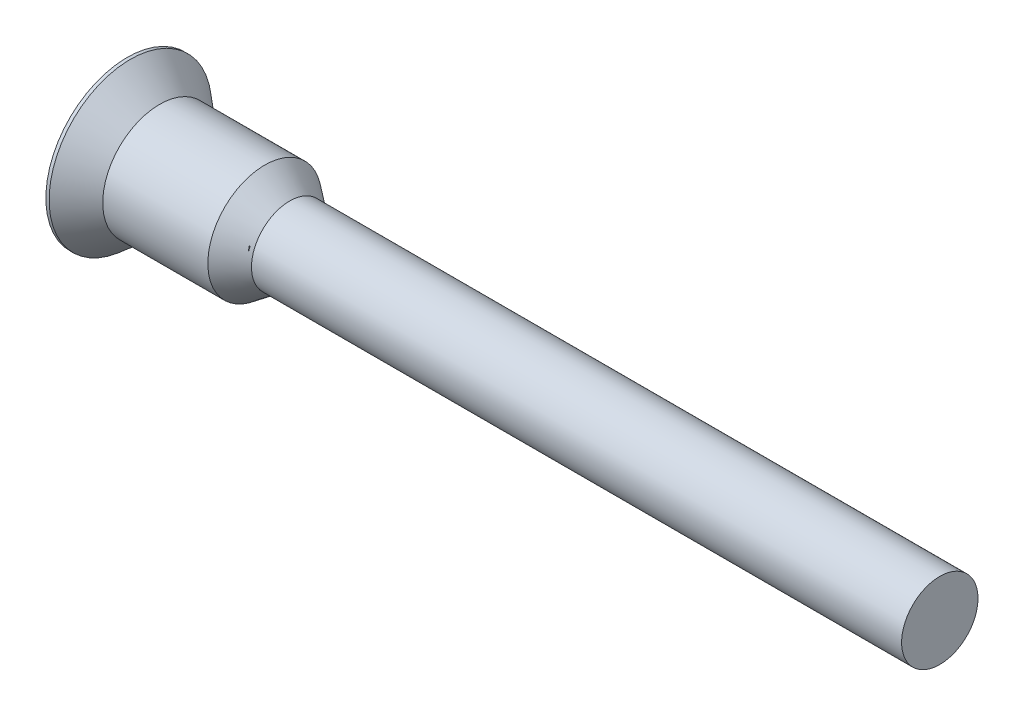
SolidWorks part; units mm, degrees
ref_plane "Front Plane" through (0, 0, 0) normal (0, 0, 1) x (1, 0, 0)
ref_plane "Top Plane" through (0, 0, 0) normal (0, 1, 0) x (1, 0, 0)
ref_plane "Right Plane" through (0, 0, 0) normal (1, 0, 0) x (0, 0, -1)
sketch "Sketch1" plane through (0, 0, 0) normal (0, 1, 0) x (1, 0, 0)
  line L0 (0, 0) -> (0, 5)
  line L2 (2, 3.5) -> (8.4667, 3.5)
  line L3 (8.4667, 3.5) -> (10, 2.35)
  line L4 (10, 2.35) -> (50, 2.35)
  line L5 (50, 2.35) -> (50, 0)
  line L6 (50, 0) -> (0, 0)
  line L7 (0, 5) -> (0.2, 5)
  line L8 (0.2, 5) -> (2, 3.5)
  dimension "D1" = 5
  dimension "D2" = 10
  dimension "D3" = 3.5
  dimension "D4" = 2.35
  dimension "D5" = 50
  dimension "D6" = 0.2
revolve "Revolve1" add sketch "Sketch1" angle 360 about L6
sketch "Sketch2" plane through (0, 0, 0) normal (-1, 0, 0) x (0, 0, 1)
  line L1 (1.9873, 1.1764) -> (-0.0252, 2.3093)
  line L2 (-0.0252, 2.3093) -> (-2.0125, 1.1328)
  line L3 (-2.0125, 1.1328) -> (-1.9873, -1.1764)
  line L4 (-1.9873, -1.1764) -> (0.0252, -2.3093)
  line L5 (0.0252, -2.3093) -> (2.0125, -1.1328)
  line L6 (2.0125, -1.1328) -> (1.9873, 1.1764)
  circle A0 centre (0, 0) radius 2 construction
  dimension "D1" = 4
extrude "Cut-Extrude1" cut sketch "Sketch2" against normal blind 2
sketch "Sketch4" plane through (50, 0, 0) normal (1, 0, 0) x (0, 0, -1)
  circle A0 centre (0, 0) radius 3.5
  dimension "D1" = 7
curve "Helix/Spiral1" pitch 1.62 height 40 turns 24.6914
sketch "Sketch6" plane through (0, 0, 0) normal (0, 1, 0) x (1, 0, 0)
  line L0 (50, 2.4749) -> (49.595, 2.4749)
  line L1 (49.595, 2.4749) -> (49.7975, 3.5)
  line L2 (49.7975, 3.5) -> (50, 2.4749)
  spline S0 degree 3 poles (50, 2.4749) (49.9665, 2.7968) (49.8986, 3.3188) (49.7975, 3.5909) (49.6962, 3.3176) (49.5949, 2.5387) (49.4937, 1.3733) (49.3924, -0.0013) (49.2911, -1.3757) (49.1899, -2.5406) (49.0886, -3.3185) (48.9873, -3.5911) (48.8861, -3.3169) (48.7848, -2.5375) (48.6835, -1.3716) (48.5823, 0.0031) (48.481, 1.3773) (48.3797, 2.5418) (48.2785, 3.3192) (48.1772, 3.5911) (48.0759, 3.3162) (47.9747, 2.5362) (47.8734, 1.37) (47.7722, -0.0048) (47.6709, -1.379) (47.5696, -2.5431) (47.4684, -3.3199) (47.3671, -3.5911) (47.2658, -3.3155) (47.1646, -2.535) (47.0633, -1.3684) (46.962, 0.0066) (46.8608, 1.3806) (46.7595, 2.5443) (46.6582, 3.3206) (46.557, 3.5911) (46.4557, 3.3148) (46.3544, 2.5337) (46.2532, 1.3667) (46.1519, -0.0084) (46.0506, -1.3822) (45.9494, -2.5456) (45.8481, -3.3212) (45.7468, -3.5911) (45.6456, -3.3142) (45.5443, -2.5325) (45.443, -1.3651) (45.3418, 0.0101) (45.2405, 1.3838) (45.1392, 2.5468) (45.038, 3.3219) (44.9367, 3.5911) (44.8354, 3.3135) (44.7342, 2.5312) (44.6329, 1.3635) (44.5316, -0.0119) (44.4304, -1.3855) (44.3291, -2.548) (44.2278, -3.3226) (44.1266, -3.5911) (44.0253, -3.3128) (43.9241, -2.53) (43.8228, -1.3618) (43.7215, 0.0137) (43.6203, 1.3871) (43.519, 2.5493) (43.4177, 3.3232) (43.3165, 3.5911) (43.2152, 3.3121) (43.1139, 2.5287) (43.0127, 1.3602) (42.9114, -0.0154) (42.8101, -1.3887) (42.7089, -2.5505) (42.6076, -3.3239) (42.5063, -3.5911) (42.4051, -3.3114) (42.3038, -2.5275) (42.2025, -1.3586) (42.1013, 0.0172) (42, 1.3903) (41.8987, 2.5518) (41.7975, 3.3246) (41.6962, 3.5911) (41.5949, 3.3107) (41.4937, 2.5262) (41.3924, 1.3569) (41.2911, -0.019) (41.1899, -1.392) (41.0886, -2.553) (40.9873, -3.3252) (40.8861, -3.5911) (40.7848, -3.3101) (40.6835, -2.5249) (40.5823, -1.3553) (40.481, 0.0207) (40.3797, 1.3936) (40.2785, 2.5542) (40.1772, 3.3259) (40.0759, 3.5911) (39.9747, 3.3094) (39.8734, 2.5237) (39.7722, 1.3537) (39.6709, -0.0225) (39.5696, -1.3952) (39.4684, -2.5555) (39.3671, -3.3266) (39.2658, -3.5911) (39.1646, -3.3087) (39.0633, -2.5224) (38.962, -1.352) (38.8608, 0.0242) (38.7595, 1.3968) (38.6582, 2.5567) (38.557, 3.3272) (38.4557, 3.5911) (38.3544, 3.308) (38.2532, 2.5212) (38.1519, 1.3504) (38.0506, -0.026) (37.9494, -1.3985) (37.8481, -2.558) (37.7468, -3.3279) (37.6456, -3.591) (37.5443, -3.3073) (37.443, -2.5199) (37.3418, -1.3488) (37.2405, 0.0278) (37.1392, 1.4001) (37.038, 2.5592) (36.9367, 3.3286) (36.8354, 3.591) (36.7342, 3.3066) (36.6329, 2.5187) (36.5316, 1.3471) (36.4304, -0.0295) (36.3291, -1.4017) (36.2278, -2.5604) (36.1266, -3.3292) (36.0253, -3.591) (35.9241, -3.3059) (35.8228, -2.5174) (35.7215, -1.3455) (35.6203, 0.0313) (35.519, 1.4033) (35.4177, 2.5617) (35.3165, 3.3299) (35.2152, 3.591) (35.1139, 3.3053) (35.0127, 2.5162) (34.9114, 1.3439) (34.8101, -0.0331) (34.7089, -1.405) (34.6076, -2.5629) (34.5063, -3.3305) (34.4051, -3.591) (34.3038, -3.3046) (34.2025, -2.5149) (34.1013, -1.3422) (34, 0.0348) (33.8987, 1.4066) (33.7975, 2.5641) (33.6962, 3.3312) (33.5949, 3.591) (33.4937, 3.3039) (33.3924, 2.5136) (33.2911, 1.3406) (33.1899, -0.0366) (33.0886, -1.4082) (32.9873, -2.5654) (32.8861, -3.3319) (32.7848, -3.591) (32.6835, -3.3032) (32.5823, -2.5124) (32.481, -1.339) (32.3797, 0.0383) (32.2785, 1.4098) (32.1772, 2.5666) (32.0759, 3.3325) (31.9747, 3.5909) (31.8734, 3.3025) (31.7722, 2.5111) (31.6709, 1.3373) (31.5696, -0.0401) (31.4684, -1.4114) (31.3671, -2.5678) (31.2658, -3.3332) (31.1646, -3.5909) (31.0633, -3.3018) (30.962, -2.5099) (30.8608, -1.3357) (30.7595, 0.0419) (30.6582, 1.4131) (30.557, 2.5691) (30.4557, 3.3338) (30.3544, 3.5909) (30.2532, 3.3011) (30.1519, 2.5086) (30.0506, 1.3341) (29.9494, -0.0436) (29.8481, -1.4147) (29.7468, -2.5703) (29.6456, -3.3345) (29.5443, -3.5909) (29.443, -3.3004) (29.3418, -2.5073) (29.2405, -1.3324) (29.1392, 0.0454) (29.038, 1.4163) (28.9367, 2.5715) (28.8354, 3.3351) (28.7342, 3.5908) (28.6329, 3.2997) (28.5316, 2.5061) (28.4304, 1.3308) (28.3291, -0.0472) (28.2278, -1.4179) (28.1266, -2.5728) (28.0253, -3.3358) (27.9241, -3.5908) (27.8228, -3.299) (27.7215, -2.5048) (27.6203, -1.3292) (27.519, 0.0489) (27.4177, 1.4195) (27.3165, 2.574) (27.2152, 3.3364) (27.1139, 3.5908) (27.0127, 3.2983) (26.9114, 2.5035) (26.8101, 1.3275) (26.7089, -0.0507) (26.6076, -1.4212) (26.5063, -2.5752) (26.4051, -3.3371) (26.3038, -3.5908) (26.2025, -3.2976) (26.1013, -2.5023) (26, -1.3259) (25.8987, 0.0524) (25.7975, 1.4228) (25.6962, 2.5764) (25.5949, 3.3377) (25.4937, 3.5908) (25.3924, 3.2969) (25.2911, 2.501) (25.1899, 1.3242) (25.0886, -0.0542) (24.9873, -1.4244) (24.8861, -2.5777) (24.7848, -3.3384) (24.6835, -3.5907) (24.5823, -3.2962) (24.481, -2.4998) (24.3797, -1.3226) (24.2785, 0.056) (24.1772, 1.426) (24.0759, 2.5789) (23.9747, 3.339) (23.8734, 3.5907) (23.7722, 3.2955) (23.6709, 2.4985) (23.5696, 1.321) (23.4684, -0.0577) (23.3671, -1.4276) (23.2658, -2.5801) (23.1646, -3.3397) (23.0633, -3.5907) (22.962, -3.2948) (22.8608, -2.4972) (22.7595, -1.3193) (22.6582, 0.0595) (22.557, 1.4293) (22.4557, 2.5814) (22.3544, 3.3403) (22.2532, 3.5906) (22.1519, 3.2941) (22.0506, 2.496) (21.9494, 1.3177) (21.8481, -0.0613) (21.7468, -1.4309) (21.6456, -2.5826) (21.5443, -3.341) (21.443, -3.5906) (21.3418, -3.2934) (21.2405, -2.4947) (21.1392, -1.316) (21.038, 0.063) (20.9367, 1.4325) (20.8354, 2.5838) (20.7342, 3.3416) (20.6329, 3.5906) (20.5316, 3.2927) (20.4304, 2.4934) (20.3291, 1.3144) (20.2278, -0.0648) (20.1266, -1.4341) (20.0253, -2.585) (19.9241, -3.3423) (19.8228, -3.5905) (19.7215, -3.292) (19.6203, -2.4921) (19.519, -1.3128) (19.4177, 0.0666) (19.3165, 1.4357) (19.2152, 2.5863) (19.1139, 3.3429) (19.0127, 3.5905) (18.9114, 3.2913) (18.8101, 2.4909) (18.7089, 1.3111) (18.6076, -0.0683) (18.5063, -1.4373) (18.4051, -2.5875) (18.3038, -3.3436) (18.2025, -3.5905) (18.1013, -3.2906) (18, -2.4896) (17.8987, -1.3095) (17.7975, 0.0701) (17.6962, 1.439) (17.5949, 2.5887) (17.4937, 3.3442) (17.3924, 3.5904) (17.2911, 3.2899) (17.1899, 2.4883) (17.0886, 1.3078) (16.9873, -0.0718) (16.8861, -1.4406) (16.7848, -2.5899) (16.6835, -3.3449) (16.5823, -3.5904) (16.481, -3.2892) (16.3797, -2.4871) (16.2785, -1.3062) (16.1772, 0.0736) (16.0759, 1.4422) (15.9747, 2.5911) (15.8734, 3.3455) (15.7722, 3.5904) (15.6709, 3.2885) (15.5696, 2.4858) (15.4684, 1.3045) (15.3671, -0.0754) (15.2658, -1.4438) (15.1646, -2.5924) (15.0633, -3.3461) (14.962, -3.5903) (14.8608, -3.2878) (14.7595, -2.4845) (14.6582, -1.3029) (14.557, 0.0771) (14.4557, 1.4454) (14.3544, 2.5936) (14.2532, 3.3468) (14.1519, 3.5903) (14.0506, 3.2871) (13.9494, 2.4832) (13.8481, 1.3013) (13.7468, -0.0789) (13.6456, -1.447) (13.5443, -2.5948) (13.443, -3.3474) (13.3418, -3.5903) (13.2405, -3.2864) (13.1392, -2.482) (13.038, -1.2996) (12.9367, 0.0807) (12.8354, 1.4486) (12.7342, 2.596) (12.6329, 3.3481) (12.5316, 3.5902) (12.4304, 3.2856) (12.3291, 2.4807) (12.2278, 1.298) (12.1266, -0.0824) (12.0253, -1.4503) (11.9241, -2.5972) (11.8228, -3.3487) (11.7215, -3.5902) (11.6203, -3.2849) (11.519, -2.4794) (11.4177, -1.2963) (11.3165, 0.0842) (11.2152, 1.4519) (11.1139, 2.5985) (11.0127, 3.3493) (10.9114, 3.5901) (10.8101, 3.2842) (10.7089, 2.4781) (10.6076, 1.2947) (10.5063, -0.0859) (10.4051, -1.4535) (10.3038, -2.5997) (10.2025, -3.3498) (10.1014, -3.5906) (10.0335, -3.3845) (10, -3.2002) knots 0 0 0 0 0.002532 0.005063 0.007595 0.010127 0.012658 0.01519 0.017722 0.020253 0.022785 0.025316 0.027848 0.03038 0.032911 0.035443 0.037975 0.040506 0.043038 0.04557 0.048101 0.050633 0.053165 0.055696 0.058228 0.060759 0.063291 0.065823 0.068354 0.070886 0.073418 0.075949 0.078481 0.081013 0.083544 0.086076 0.088608 0.091139 0.093671 0.096203 0.098734 0.101266 0.103797 0.106329 0.108861 0.111392 0.113924 0.116456 0.118987 0.121519 0.124051 0.126582 0.129114 0.131646 0.134177 0.136709 0.139241 0.141772 0.144304 0.146835 0.149367 0.151899 0.15443 0.156962 0.159494 0.162025 0.164557 0.167089 0.16962 0.172152 0.174684 0.177215 0.179747 0.182278 0.18481 0.187342 0.189873 0.192405 0.194937 0.197468 0.2 0.202532 0.205063 0.207595 0.210127 0.212658 0.21519 0.217722 0.220253 0.222785 0.225316 0.227848 0.23038 0.232911 0.235443 0.237975 0.240506 0.243038 0.24557 0.248101 0.250633 0.253165 0.255696 0.258228 0.260759 0.263291 0.265823 0.268354 0.270886 0.273418 0.275949 0.278481 0.281013 0.283544 0.286076 0.288608 0.291139 0.293671 0.296203 0.298734 0.301266 0.303797 0.306329 0.308861 0.311392 0.313924 0.316456 0.318987 0.321519 0.324051 0.326582 0.329114 0.331646 0.334177 0.336709 0.339241 0.341772 0.344304 0.346835 0.349367 0.351899 0.35443 0.356962 0.359494 0.362025 0.364557 0.367089 0.36962 0.372152 0.374684 0.377215 0.379747 0.382278 0.38481 0.387342 0.389873 0.392405 0.394937 0.397468 0.4 0.402532 0.405063 0.407595 0.410127 0.412658 0.41519 0.417722 0.420253 0.422785 0.425316 0.427848 0.43038 0.432911 0.435443 0.437975 0.440506 0.443038 0.44557 0.448101 0.450633 0.453165 0.455696 0.458228 0.460759 0.463291 0.465823 0.468354 0.470886 0.473418 0.475949 0.478481 0.481013 0.483544 0.486076 0.488608 0.491139 0.493671 0.496203 0.498734 0.501266 0.503797 0.506329 0.508861 0.511392 0.513924 0.516456 0.518987 0.521519 0.524051 0.526582 0.529114 0.531646 0.534177 0.536709 0.539241 0.541772 0.544304 0.546835 0.549367 0.551899 0.55443 0.556962 0.559494 0.562025 0.564557 0.567089 0.56962 0.572152 0.574684 0.577215 0.579747 0.582278 0.58481 0.587342 0.589873 0.592405 0.594937 0.597468 0.6 0.602532 0.605063 0.607595 0.610127 0.612658 0.61519 0.617722 0.620253 0.622785 0.625316 0.627848 0.63038 0.632911 0.635443 0.637975 0.640506 0.643038 0.64557 0.648101 0.650633 0.653165 0.655696 0.658228 0.660759 0.663291 0.665823 0.668354 0.670886 0.673418 0.675949 0.678481 0.681013 0.683544 0.686076 0.688608 0.691139 0.693671 0.696203 0.698734 0.701266 0.703797 0.706329 0.708861 0.711392 0.713924 0.716456 0.718987 0.721519 0.724051 0.726582 0.729114 0.731646 0.734177 0.736709 0.739241 0.741772 0.744304 0.746835 0.749367 0.751899 0.75443 0.756962 0.759494 0.762025 0.764557 0.767089 0.76962 0.772152 0.774684 0.777215 0.779747 0.782278 0.78481 0.787342 0.789873 0.792405 0.794937 0.797468 0.8 0.802532 0.805063 0.807595 0.810127 0.812658 0.81519 0.817722 0.820253 0.822785 0.825316 0.827848 0.83038 0.832911 0.835443 0.837975 0.840506 0.843038 0.84557 0.848101 0.850633 0.853165 0.855696 0.858228 0.860759 0.863291 0.865823 0.868354 0.870886 0.873418 0.875949 0.878481 0.881013 0.883544 0.886076 0.888608 0.891139 0.893671 0.896203 0.898734 0.901266 0.903797 0.906329 0.908861 0.911392 0.913924 0.916456 0.918987 0.921519 0.924051 0.926582 0.929114 0.931646 0.934177 0.936709 0.939241 0.941772 0.944304 0.946835 0.949367 0.951899 0.95443 0.956962 0.959494 0.962025 0.964557 0.967089 0.96962 0.972152 0.974684 0.977215 0.979747 0.982278 0.98481 0.987342 0.989873 0.992405 0.994937 0.997468 1 1 1 1 construction
sweep "Cut-Sweep6" cut profiles "Sketch6" path "Helix/Spiral1"
